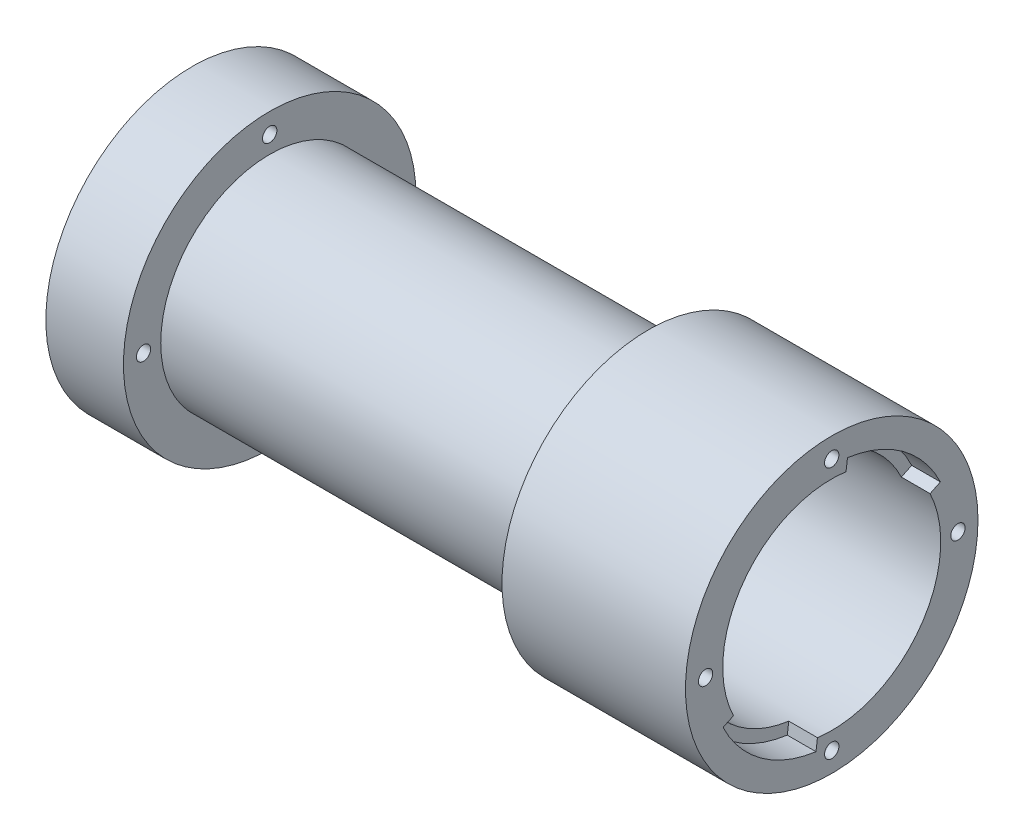
SolidWorks part; units mm, degrees
ref_plane "前视基准面" through (0, 0, 0) normal (0, 0, 1) x (1, 0, 0)
ref_plane "上视基准面" through (0, 0, 0) normal (0, 1, 0) x (1, 0, 0)
ref_plane "右视基准面" through (0, 0, 0) normal (1, 0, 0) x (0, 0, -1)
sketch "草图1" plane through (0, 0, 0) normal (1, 0, 0) x (0, 0, -1)
  circle A0 centre (0, 0) radius 31
  circle A1 centre (0, 0) radius 51
extrude "凸台-拉伸1" add sketch "草图1" along normal blind 18 and the other way blind 9.06
sketch "草图2" plane through (18, 0, 0) normal (1, 0, 0) x (0, 0, -1)
  circle A0 centre (0, 0) radius 27
  circle A1 centre (0, 0) radius 38
extrude "凸台-拉伸2" add sketch "草图2" along normal blind 132
sketch "草图3" plane through (150, 0, 0) normal (1, 0, 0) x (0, 0, -1)
  circle A0 centre (0, 0) radius 38
  circle A1 centre (0, 0) radius 51
extrude "凸台-拉伸3" add sketch "草图3" along normal blind 63.98 separate body
sketch "草图4" plane through (-9.06, 0, 0) normal (-1, 0, 0) x (0, 0, 1)
  line L0 (0, 0) -> (60.5842, 0) construction
  line L1 (60.5842, 0) -> (-61.6406, 0) construction
  line L2 (0, 0) -> (0, 71.2022) construction
  line L3 (0, 71.2022) -> (0, -60.4245) construction
  circle A0 centre (0, 44) radius 2.5
  circle A1 centre (44, 0) radius 2.5
  circle A2 centre (0, -44) radius 2.5
  circle A3 centre (-44, 0) radius 2.5
  point P17 (0, 0)
  dimension "D1" = 4
extrude "切除-拉伸1" cut sketch "草图4" against normal up to surface (223.04 mm away)
sketch "草图5" plane through (213.98, 0, 0) normal (1, 0, 0) x (0, 0, -1)
  line L12 (4.9791, 37.6724) -> (5.5032, 41.6379)
  line L13 (34.278, 16.4018) -> (37.8862, 18.1283)
  line L14 (-4.9791, -37.6724) -> (-5.5032, -41.6379)
  line L15 (-34.278, -16.4018) -> (-37.8862, -18.1283)
  arc A2 (34.278, 16.4018) -> (29.8966, 23.4563) centre (0, 0) ccw
  circle A3 centre (0, 0) radius 38 construction
  arc A5 (-34.278, -16.4018) -> (-29.8966, -23.4563) centre (0, 0) ccw
  arc A6 (16.9401, 34.0152) -> (29.8966, 23.4563) centre (0, 0) cw
  arc A10 (18.7233, 37.5957) -> (33.0436, 25.9253) centre (0, 0) cw
  arc A15 (18.7233, 37.5957) -> (5.5032, 41.6379) centre (0, 0) ccw
  arc A16 (33.0436, 25.9253) -> (37.8862, 18.1283) centre (0, 0) cw
  arc A17 (16.9401, 34.0152) -> (4.9791, 37.6724) centre (0, 0) ccw
  arc A18 (-16.9401, -34.0152) -> (-29.8966, -23.4563) centre (0, 0) cw
  arc A19 (-18.7233, -37.5957) -> (-33.0436, -25.9253) centre (0, 0) cw
  arc A20 (-18.7233, -37.5957) -> (-5.5032, -41.6379) centre (0, 0) ccw
  arc A21 (-33.0436, -25.9253) -> (-37.8862, -18.1283) centre (0, 0) cw
  arc A22 (-16.9401, -34.0152) -> (-4.9791, -37.6724) centre (0, 0) ccw
  point P22 (0, 0)
  point P27 (0, 0)
extrude "切除-拉伸2" cut sketch "草图5" against normal blind 10
sketch "草图6" plane through (150, 0, 0) normal (1, 0, 0) x (0, 0, -1)
  circle A0 centre (0, 0) radius 31
extrude "切除-拉伸3" cut sketch "草图6" against normal blind 14
